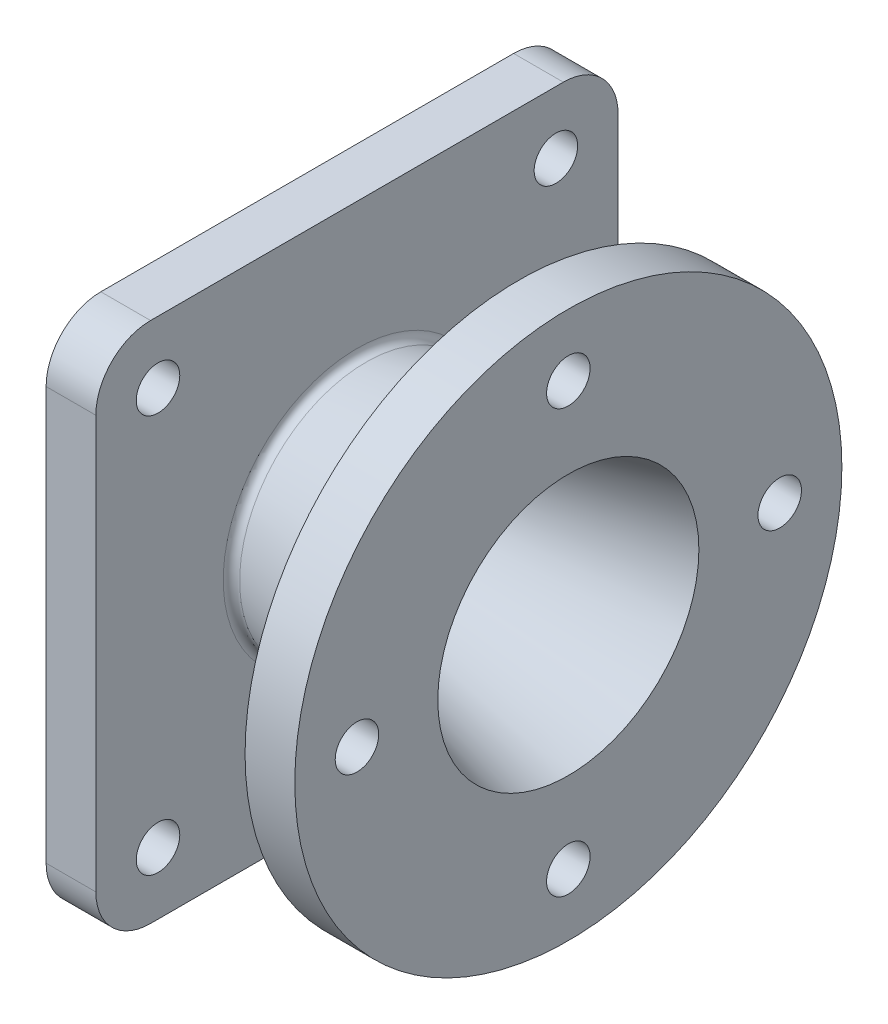
SolidWorks part; units mm, degrees
material "Сталь"
ref_plane "Спереди" through (0, 0, 0) normal (0, 0, 1) x (1, 0, 0)
ref_plane "Сверху" through (0, 0, 0) normal (0, 1, 0) x (1, 0, 0)
ref_plane "Справа" through (0, 0, 0) normal (1, 0, 0) x (0, 0, -1)
sketch "Эскиз1" plane through (0, 0, 0) normal (0, 0, 1) x (1, 0, 0)
  line L0 (0, 0) -> (-243.1706, 0) construction
  line L1 (0, 52.5) -> (0, 110)
  line L2 (0, 110) -> (-20, 110)
  line L3 (-20, 110) -> (-20, 65)
  line L4 (-85, 50) -> (-20, 65)
  line L5 (-105, 35) -> (-113, 35)
  line L6 (-85, 50) -> (-85, 105)
  line L7 (-85, 105) -> (-105, 105)
  line L8 (-105, 105) -> (-105, 62.5)
  line L9 (-105, 62.5) -> (-130, 62.5)
  line L10 (-130, 62.5) -> (-130, 28.7125)
  line L11 (-113, 35) -> (-113, 28.7125)
  line L12 (0, 52.5) -> (-105, 25)
  line L13 (-105, 25) -> (-105, 35)
  line L14 (-113, 28.7125) -> (-130, 28.7125)
  dimension "D1" = 220
  dimension "D2" = 20
  dimension "D3" = 105
  dimension "D4" = 100
  dimension "D5" = 130
  dimension "D6" = 65
  dimension "D7" = 25
  dimension "D8" = 210
  dimension "D9" = 105
  dimension "D10" = 125
  dimension "D11" = 70
  dimension "D12" = 50
  dimension "D13" = 57.425
  dimension "D14" = 8
revolve "Повернуть1" add sketch "Эскиз1" angle 360 about L0
cosmetic thread "Условное изображение резьбы1" parameters "D2"=64
sketch "Эскиз2" plane through (0, 0, 0) normal (1, 0, 0) x (0, 0, -1)
  circle A0 centre (0, 85) radius 8.75
  dimension "D2" = 17.5
  dimension "D1" = 85
extrude "Вырез-Вытянуть1" cut sketch "Эскиз2" against normal up to next
pattern_circular "Круговой массив1" count 4 over 360 about axis through (0, 0, 0) along (1, 0, 0) of "Вырез-Вытянуть1"
sketch "Эскиз3" plane through (-105, 0, 0) normal (-1, 0, 0) x (0, 0, 1)
  line L1 (-105, -105) -> (105, -105)
  line L2 (-105, -105) -> (-105, 105)
  line L3 (-105, 105) -> (105, 105)
  line L4 (105, -105) -> (105, 105)
  line L5 (-105, -105) -> (105, 105) construction
  line L6 (-105, 105) -> (105, -105) construction
  circle A4 centre (0, 0) radius 105 construction
  circle A5 centre (0, 0) radius 35 construction
  circle A6 centre (0, 0) radius 35
  point P0 (0, 0)
extrude "Бобышка-Вытянуть1" add sketch "Эскиз3" against normal up to surface (20 mm away) up to face at (-85, 0, -105)
sketch "Эскиз4" plane through (-105, 0, 0) normal (-1, 0, 0) x (0, 0, 1)
  line L0 (0, 0) -> (105, 105) construction
  circle A0 centre (80, 80) radius 8.75
  dimension "D1" = 80
  dimension "D2" = 17.5
extrude "Вырез-Вытянуть2" cut sketch "Эскиз4" against normal up to surface (20 mm away) up to face at (-85, 0, 0)
fillet "Скругление1" radius 22 4 edges at (-95, 105, -105) (-95, -105, -105) (-95, -105, 105) (-95, 105, 105)
pattern_circular "Круговой массив5" count 4 over 360 about axis through (0, 0, 0) along (1, 0, 0) of "Вырез-Вытянуть2"
chamfer "Фаска1" distance 3.2875 angle 45 1 edges at (-130, 0, -28.7125)
fillet "Скругление2" radius 3 2 edges at (-20, 0, -65) (-85, 0, -50)
